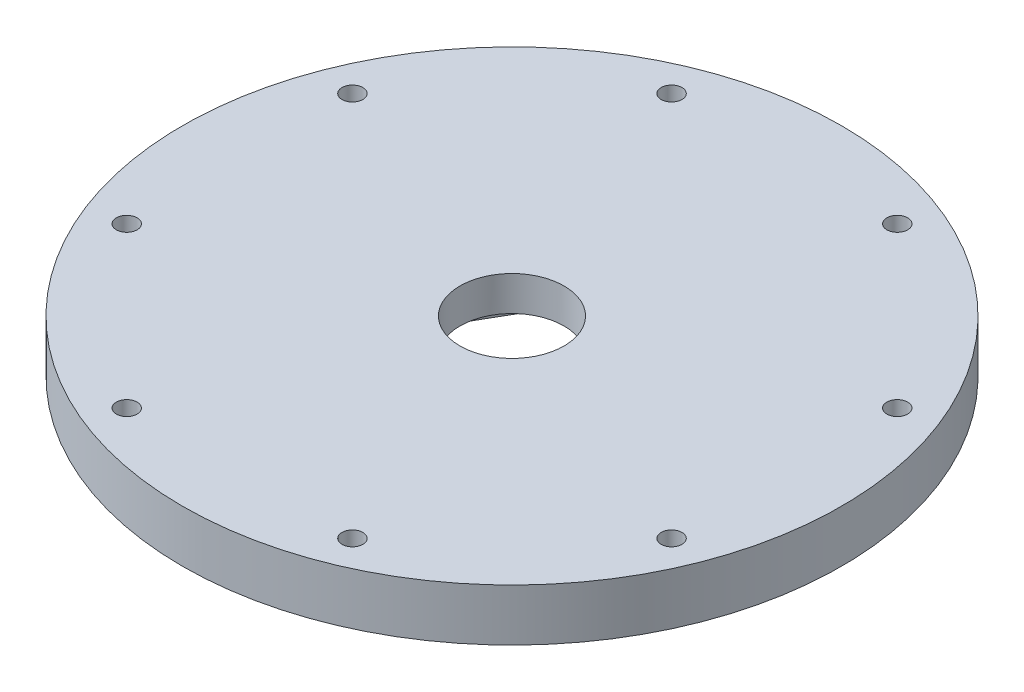
SolidWorks part; units mm, degrees
ref_plane "Ön Düzlem" through (0, 0, 0) normal (0, 0, 1) x (1, 0, 0)
ref_plane "Üst Düzlem" through (0, 0, 0) normal (0, 1, 0) x (1, 0, 0)
ref_plane "Sağ Düzlem" through (0, 0, 0) normal (1, 0, 0) x (0, 0, -1)
sketch "Çizim1" plane through (0, 0, 0) normal (0, 1, 0) x (1, 0, 0)
  circle A0 centre (0, 0) radius 47.5
  dimension "D1" = 95
extrude "Yükseklik-Ekstrüzyon1" add sketch "Çizim1" along normal mid plane 15.5
sketch "Çizim2" plane through (0, -7.75, 0) normal (0, -1, 0) x (1, 0, 0)
  circle A0 centre (0, 0) radius 32.5
  dimension "D1" = 65
extrude "Kes-Ekstrüzyon1" cut sketch "Çizim2" against normal blind 8 flip side to cut
sketch "Çizim3" plane through (0, -7.75, 0) normal (0, -1, 0) x (1, 0, 0)
  line L0 (0, 13.2069) -> (0, 0) construction
  line L1 (15.25, 0) -> (7.625, 13.2069)
  line L2 (7.625, 13.2069) -> (-7.625, 13.2069)
  line L3 (-7.625, 13.2069) -> (-15.25, 0)
  line L4 (-15.25, 0) -> (-7.625, -13.2069)
  line L5 (-7.625, -13.2069) -> (7.625, -13.2069)
  line L6 (7.625, -13.2069) -> (15.25, 0)
  circle A1 centre (0, 0) radius 13.2069 construction
  dimension "D2" = 15.25
extrude "Kes-Ekstrüzyon2" cut sketch "Çizim3" against normal blind 10.5
sketch "Çizim4" plane through (0, -7.75, 0) normal (0, -1, 0) x (1, 0, 0)
  circle A0 centre (0, 0) radius 30
  dimension "D1" = 60
extrude "Kes-Ekstrüzyon3" cut sketch "Çizim4" against normal blind 6
sketch "Çizim5" plane through (0, 7.75, 0) normal (0, 1, 0) x (1, 0, 0)
  line L0 (-16.264, 39.2649) -> (0, 0) construction
  line L1 (0, 0) -> (0, 42.5) construction
  circle A0 centre (0, 0) radius 42.5 construction
  circle A1 centre (-16.264, 39.2649) radius 1.5
  dimension "D1" = 85
  dimension "D3" = 3
  dimension "D2" = 22.5
extrude "Kes-Ekstrüzyon4" cut sketch "Çizim5" against normal through all
pattern_circular "Dairesel Kaplama1" count 8 over 360 about axis through (0, 0, 0) along (0, 1, 0) of "Kes-Ekstrüzyon4"
sketch "Çizim6" plane through (0, 7.75, 0) normal (0, 1, 0) x (1, 0, 0)
  circle A0 centre (0, 0) radius 7.5
  dimension "D1" = 15
extrude "Kes-Ekstrüzyon5" cut sketch "Çizim6" against normal through all
